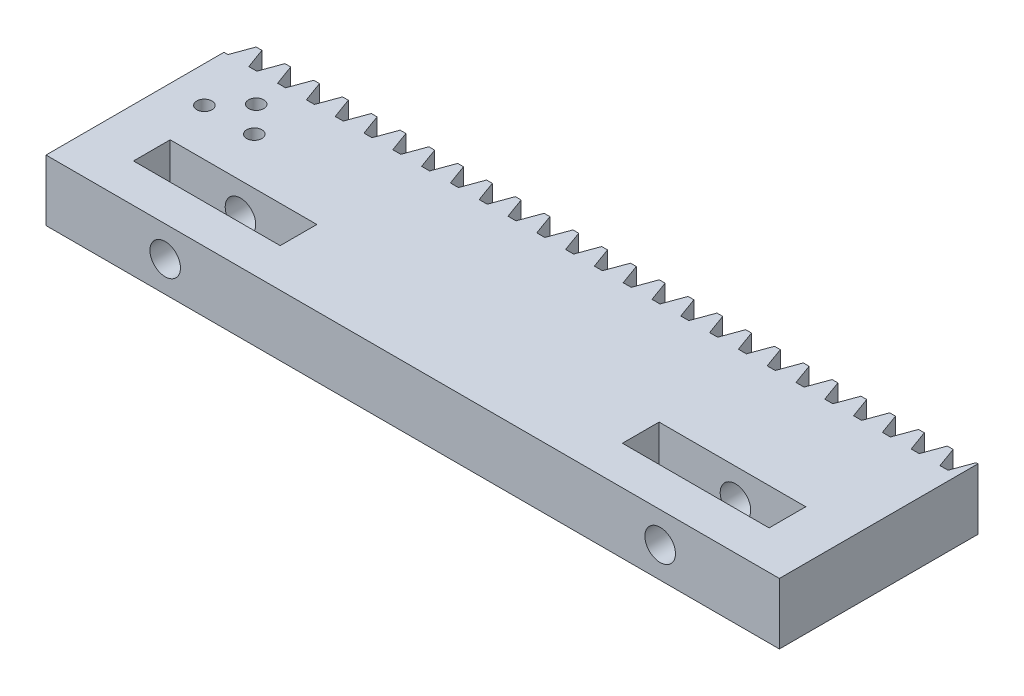
SolidWorks part; units mm, degrees
ref_plane "Front Plane" through (0, 0, 0) normal (0, 0, 1) x (1, 0, 0)
ref_plane "Top Plane" through (0, 0, 0) normal (0, 1, 0) x (1, 0, 0)
ref_plane "Right Plane" through (0, 0, 0) normal (1, 0, 0) x (0, 0, -1)
sketch "Sketch1" plane through (0, 0, 0) normal (0, 1, 0) x (1, 0, 0)
  line L0 (58.4644, 9.875) -> (57.1551, 9.875)
  line L1 (57.1551, 9.875) -> (55.9267, 13.25)
  line L2 (55.9267, 13.25) -> (54.9804, 13.25)
  line L3 (54.9804, 13.25) -> (53.752, 9.875)
  line L4 (53.752, 9.875) -> (52.4427, 9.875)
  line L5 (52.4427, 9.875) -> (51.2143, 13.25)
  line L6 (51.2143, 13.25) -> (50.268, 13.25)
  line L7 (50.268, 13.25) -> (49.0396, 9.875)
  line L8 (49.0396, 9.875) -> (47.7303, 9.875)
  line L9 (47.7303, 9.875) -> (46.5019, 13.25)
  line L10 (46.5019, 13.25) -> (45.5556, 13.25)
  line L11 (45.5556, 13.25) -> (44.3272, 9.875)
  line L12 (44.3272, 9.875) -> (43.0179, 9.875)
  line L13 (43.0179, 9.875) -> (41.7895, 13.25)
  line L14 (41.7895, 13.25) -> (40.8432, 13.25)
  line L15 (40.8432, 13.25) -> (39.6148, 9.875)
  line L16 (39.6148, 9.875) -> (38.3055, 9.875)
  line L17 (38.3055, 9.875) -> (37.0771, 13.25)
  line L18 (37.0771, 13.25) -> (36.1308, 13.25)
  line L19 (36.1308, 13.25) -> (34.9024, 9.875)
  line L20 (34.9024, 9.875) -> (33.5931, 9.875)
  line L21 (33.5931, 9.875) -> (32.3647, 13.25)
  line L22 (32.3647, 13.25) -> (31.4184, 13.25)
  line L23 (31.4184, 13.25) -> (30.19, 9.875)
  line L24 (30.19, 9.875) -> (28.8807, 9.875)
  line L25 (28.8807, 9.875) -> (27.6523, 13.25)
  line L26 (27.6523, 13.25) -> (26.7061, 13.25)
  line L27 (26.7061, 13.25) -> (25.4777, 9.875)
  line L28 (25.4777, 9.875) -> (24.1683, 9.875)
  line L29 (24.1683, 9.875) -> (22.9399, 13.25)
  line L30 (22.9399, 13.25) -> (21.9937, 13.25)
  line L31 (21.9937, 13.25) -> (20.7653, 9.875)
  line L32 (20.7653, 9.875) -> (19.456, 9.875)
  line L33 (19.456, 9.875) -> (18.2276, 13.25)
  line L34 (18.2276, 13.25) -> (17.2813, 13.25)
  line L35 (17.2813, 13.25) -> (16.0529, 9.875)
  line L36 (16.0529, 9.875) -> (14.7436, 9.875)
  line L37 (14.7436, 9.875) -> (13.5152, 13.25)
  line L38 (13.5152, 13.25) -> (12.5689, 13.25)
  line L39 (12.5689, 13.25) -> (11.3405, 9.875)
  line L40 (11.3405, 9.875) -> (10.0312, 9.875)
  line L41 (10.0312, 9.875) -> (8.8028, 13.25)
  line L42 (8.8028, 13.25) -> (7.8565, 13.25)
  line L43 (7.8565, 13.25) -> (6.6281, 9.875)
  line L44 (6.6281, 9.875) -> (5.3188, 9.875)
  line L45 (5.3188, 9.875) -> (4.0904, 13.25)
  line L46 (4.0904, 13.25) -> (3.1441, 13.25)
  line L47 (3.1441, 13.25) -> (1.9157, 9.875)
  line L48 (1.9157, 9.875) -> (0.6064, 9.875)
  line L49 (0.6064, 9.875) -> (-0.622, 13.25)
  line L50 (-0.622, 13.25) -> (-1.5683, 13.25)
  line L51 (-1.5683, 13.25) -> (-2.7967, 9.875)
  line L52 (-2.7967, 9.875) -> (-4.106, 9.875)
  line L53 (-4.106, 9.875) -> (-5.3344, 13.25)
  line L54 (-5.3344, 13.25) -> (-6.2807, 13.25)
  line L55 (-6.2807, 13.25) -> (-7.5091, 9.875)
  line L56 (-7.5091, 9.875) -> (-8.8184, 9.875)
  line L57 (-8.8184, 9.875) -> (-10.0468, 13.25)
  line L58 (-10.0468, 13.25) -> (-10.9931, 13.25)
  line L59 (-10.9931, 13.25) -> (-12.2215, 9.875)
  line L60 (-12.2215, 9.875) -> (-13.5308, 9.875)
  line L61 (-13.5308, 9.875) -> (-14.7592, 13.25)
  line L62 (-14.7592, 13.25) -> (-15.7054, 13.25)
  line L63 (-15.7054, 13.25) -> (-16.9338, 9.875)
  line L64 (-16.9338, 9.875) -> (-18.2432, 9.875)
  line L65 (-18.2432, 9.875) -> (-19.4716, 13.25)
  line L66 (-19.4716, 13.25) -> (-20.4178, 13.25)
  line L67 (-20.4178, 13.25) -> (-21.6462, 9.875)
  line L68 (-21.6462, 9.875) -> (-22.9555, 9.875)
  line L69 (-22.9555, 9.875) -> (-24.1839, 13.25)
  line L70 (-24.1839, 13.25) -> (-25.1302, 13.25)
  line L71 (-25.1302, 13.25) -> (-26.3586, 9.875)
  line L72 (-26.3586, 9.875) -> (-27.6679, 9.875)
  line L73 (-27.6679, 9.875) -> (-28.8963, 13.25)
  line L74 (-28.8963, 13.25) -> (-29.8426, 13.25)
  line L75 (-29.8426, 13.25) -> (-31.071, 9.875)
  line L76 (-31.071, 9.875) -> (-32.3803, 9.875)
  line L77 (-32.3803, 9.875) -> (-33.6087, 13.25)
  line L78 (-33.6087, 13.25) -> (-34.555, 13.25)
  line L79 (-34.555, 13.25) -> (-35.7834, 9.875)
  line L80 (-35.7834, 9.875) -> (-37.0927, 9.875)
  line L81 (-37.0927, 9.875) -> (-38.3211, 13.25)
  line L82 (-38.3211, 13.25) -> (-39.2674, 13.25)
  line L83 (-39.2674, 13.25) -> (-40.4958, 9.875)
  line L84 (-40.4958, 9.875) -> (-41.8051, 9.875)
  line L85 (-41.8051, 9.875) -> (-43.0335, 13.25)
  line L86 (-43.0335, 13.25) -> (-43.9798, 13.25)
  line L87 (-43.9798, 13.25) -> (-45.2082, 9.875)
  line L88 (-45.2082, 9.875) -> (-46.5175, 9.875)
  line L89 (-46.5175, 9.875) -> (-47.7459, 13.25)
  line L90 (-47.7459, 13.25) -> (-48.6922, 13.25)
  line L91 (-48.6922, 13.25) -> (-49.9206, 9.875)
  line L92 (-49.9206, 9.875) -> (-51.2299, 9.875)
  line L93 (-51.2299, 9.875) -> (-52.4583, 13.25)
  line L94 (-52.4583, 13.25) -> (-53.4046, 13.25)
  line L95 (-53.4046, 13.25) -> (-54.633, 9.875)
  line L96 (-54.633, 9.875) -> (-55.9423, 9.875)
  line L97 (-55.9423, 9.875) -> (-57.1707, 13.25)
  line L98 (-57.1707, 13.25) -> (-58.1169, 13.25)
  line L99 (-58.1169, 13.25) -> (-59.3453, 9.875)
  line L100 (-59.3453, 9.875) -> (-60, 9.875)
  line L101 (-60, 9.875) -> (-60, -13.25)
  line L102 (-60, -13.25) -> (60, -13.25)
  line L103 (60, -13.25) -> (60, 13.25)
  line L104 (60, 13.25) -> (59.6928, 13.25)
  line L105 (59.6928, 13.25) -> (58.4644, 9.875)
extrude "Boss-Extrude1" add sketch "Sketch1" along normal mid plane 10
sketch "Sketch3" plane through (0, 5, 0) normal (0, 1, 0) x (1, 0, 0)
  line L1 (-60, -13.25) -> (60, -13.25)
  line L2 (-60, -13.25) -> (-60, -19.25)
  line L3 (-60, -19.25) -> (60, -19.25)
  line L4 (60, -13.25) -> (60, -19.25)
  dimension "D1" = 6
extrude "Boss-Extrude2" add sketch "Sketch3" against normal blind 10
sketch "Sketch4" plane through (0, 5, 0) normal (0, 1, 0) x (1, 0, 0)
  line L0 (-66.6571, -12.6829) -> (-66.6571, -7.1829) construction
  line L1 (-66.6571, -9.9329) -> (96.7972, -9.9329) construction
  line L2 (96.7972, -9.9329) -> (115.9908, -7.1829) construction
sketch "Sketch5" plane through (0, 5, 0) normal (0, 1, 0) x (1, 0, 0)
  line L0 (-60, -9.9329) -> (60, -9.9329) construction
  line L1 (-66.6571, -9.9329) -> (96.7972, -9.9329) construction
  line L2 (-60, 9.875) -> (-60, -19.25) construction
  line L3 (60, -19.25) -> (60, 13.25) construction
  line L4 (0, -9.9329) -> (0, 6.901) construction
  line L5 (52, -12.9329) -> (28, -6.9329) construction
  line L6 (-52, -6.9329) -> (-28, -6.9329)
  line L7 (-52, -6.9329) -> (-52, -12.9329)
  line L8 (-52, -12.9329) -> (-28, -12.9329)
  line L9 (-28, -6.9329) -> (-28, -12.9329)
  line L10 (-52, -6.9329) -> (-28, -12.9329) construction
  line L11 (-52, -12.9329) -> (-28, -6.9329) construction
  line L12 (52, -6.9329) -> (28, -12.9329) construction
  line L13 (28, -6.9329) -> (28, -12.9329)
  line L14 (52, -12.9329) -> (28, -12.9329)
  line L15 (52, -6.9329) -> (52, -12.9329)
  line L16 (52, -6.9329) -> (28, -6.9329)
  point P8 (-40, -9.9329)
  point P11 (0, -9.9329)
  point P21 (40, -9.9329)
  dimension "D1" = 24
  dimension "D2" = 6
  dimension "D3" = 40
extrude "Cut-Extrude1" cut sketch "Sketch5" against normal blind 10
sketch "Sketch7" plane through (0, 0, 6.9329) normal (0, 0, 1) x (1, 0, 0)
  line L0 (-40.4958, 5) -> (-40.4958, -5) construction
  circle A0 centre (-40.4958, 0) radius 2.5
  dimension "D1" = 5
extrude "Cut-Extrude2" cut sketch "Sketch7" along normal blind 20 and the other way blind 5
mirror "Mirror1" about plane through (0, 0, 0) normal (1, 0, 0) of "Cut-Extrude2"
sketch "Sketch8" plane through (0, 5, 0) normal (0, 1, 0) x (1, 0, 0)
  circle A0 centre (-54.0819, 0.75) radius 1.25
  circle A1 centre (-45.9181, 0.75) radius 1.25
  dimension "D1" = 2.5
  dimension "D2" = 2.5
extrude "Cut-Extrude3" cut sketch "Sketch8" against normal blind 20
sketch "Sketch9" plane through (0, 5, 0) normal (0, 1, 0) x (1, 0, 0)
  line L0 (-54.0819, 0.75) -> (-45.9181, 0.75) construction
  line L1 (-45.9181, 0.75) -> (-50, 5.1475) construction
  line L2 (-50, 5.1475) -> (-54.0819, 0.75) construction
  line L3 (-50, 5.1475) -> (-50, 0.75) construction
  circle A0 centre (-50, 5.1475) radius 1.25
  dimension "D2" = 2.5
  dimension "D1" = 6
extrude "Cut-Extrude4" cut sketch "Sketch9" against normal blind 10
